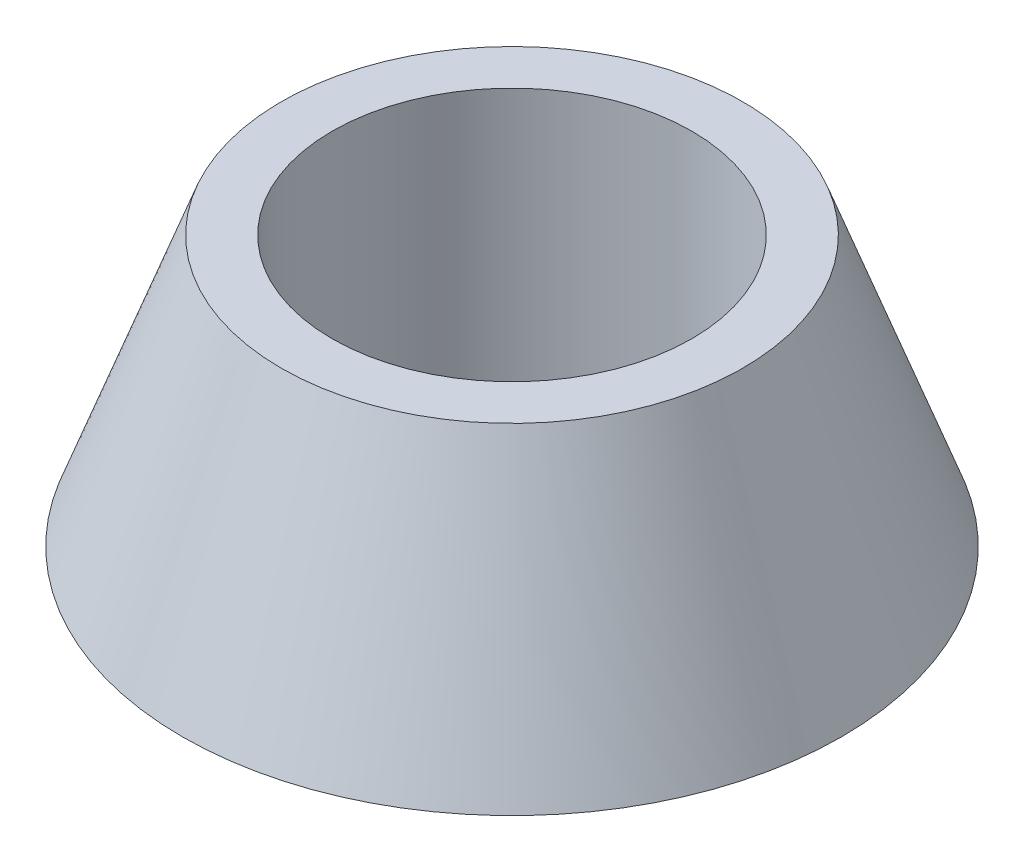
SolidWorks part; units mm, degrees
material "1.0545 (S355N)"
ref_plane "Płaszczyzna przednia" through (0, 0, 0) normal (0, 0, 1) x (1, 0, 0)
ref_plane "Płaszczyzna górna" through (0, 0, 0) normal (0, 1, 0) x (1, 0, 0)
ref_plane "Płaszczyzna prawa" through (0, 0, 0) normal (1, 0, 0) x (0, 0, -1)
sketch "Szkic1" plane through (0, 0, 0) normal (0, 0, 1) x (1, 0, 0)
  line L0 (6, 4.5) -> (6, -4.5)
  line L1 (6, -4.5) -> (11, -4.5)
  line L2 (11, -4.5) -> (7.7, 4.5)
  line L3 (7.7, 4.5) -> (6, 4.5)
  line L4 (0, 7.9207) -> (0, -9.5499) construction
  point P2 (6, 0)
  dimension "D1" = 6
  dimension "D2" = 7.7
  dimension "D3" = 11
  dimension "D4" = 9
revolve "Obrót1" add sketch "Szkic1" angle 360 about L4
